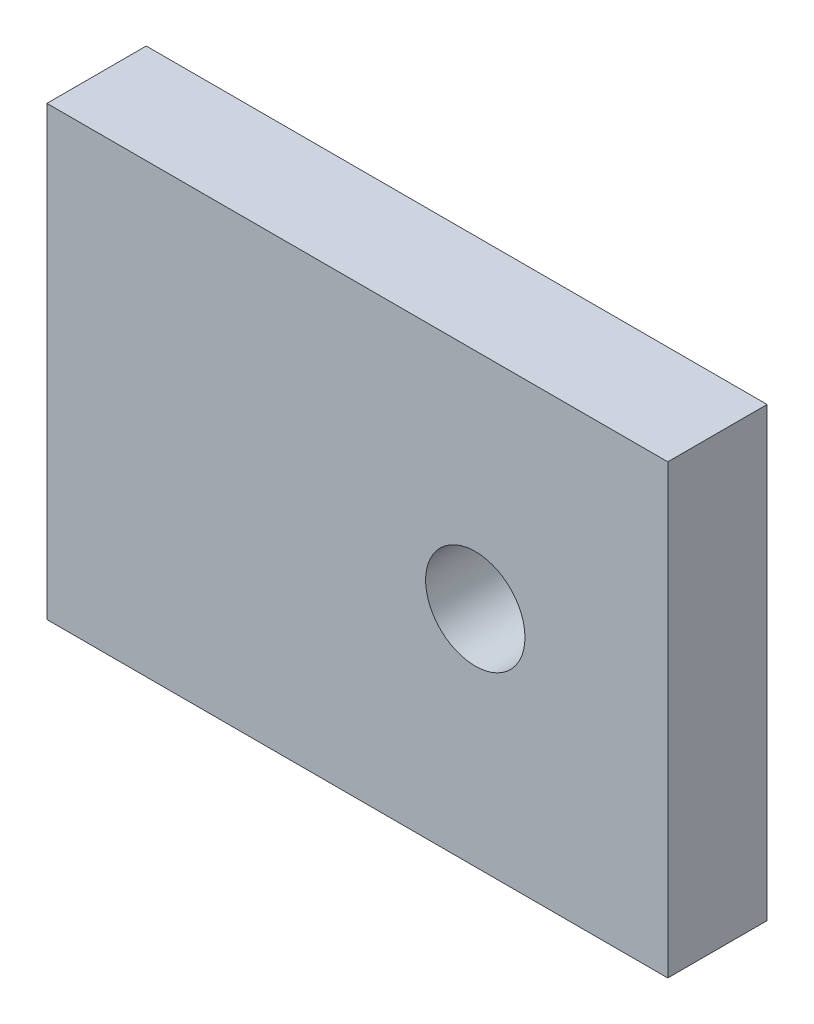
SolidWorks part; units mm, degrees
ref_plane "Płaszczyzna przednia" through (0, 0, 0) normal (0, 0, 1) x (1, 0, 0)
ref_plane "Płaszczyzna górna" through (0, 0, 0) normal (0, 1, 0) x (1, 0, 0)
ref_plane "Płaszczyzna prawa" through (0, 0, 0) normal (1, 0, 0) x (0, 0, -1)
sketch "Szkic1" plane through (0, 0, 0) normal (0, 0, 1) x (1, 0, 0)
  line L1 (-12.5, -9) -> (12.5, -9)
  line L2 (-12.5, -9) -> (-12.5, 9)
  line L3 (-12.5, 9) -> (12.5, 9)
  line L4 (12.5, -9) -> (12.5, 9)
  line L5 (0, 9) -> (0, -9) construction
  line L6 (-12.5, 0) -> (12.5, 0) construction
  point P0 (0, 0)
  dimension "D1" = 25
  dimension "D2" = 18
extrude "Dodanie-wyciągnięcie1" add sketch "Szkic1" along normal blind 4
sketch "Szkic2" plane through (0, 0, 4) normal (0, 0, 1) x (1, 0, 0)
  line L0 (12.5, -9) -> (12.5, 9) construction
  line L1 (10.25, -5) -> (-0.75, -5) construction
  line L2 (10.25, -5) -> (10.25, 5) construction
  line L3 (10.25, 5) -> (-0.75, 5) construction
  line L4 (-0.75, -5) -> (-0.75, 5) construction
  line L5 (-12.5, -9) -> (12.5, -9) construction
  line L6 (-0.75, -5) -> (10.25, 5) construction
  circle A0 centre (4.75, 0) radius 2
  dimension "D5" = 4
  dimension "D1" = 2.25
  dimension "D2" = 4
  dimension "D3" = 10
  dimension "D4" = 11
extrude "Wytnij-wyciągnięcie1" cut sketch "Szkic2" against normal up to next
